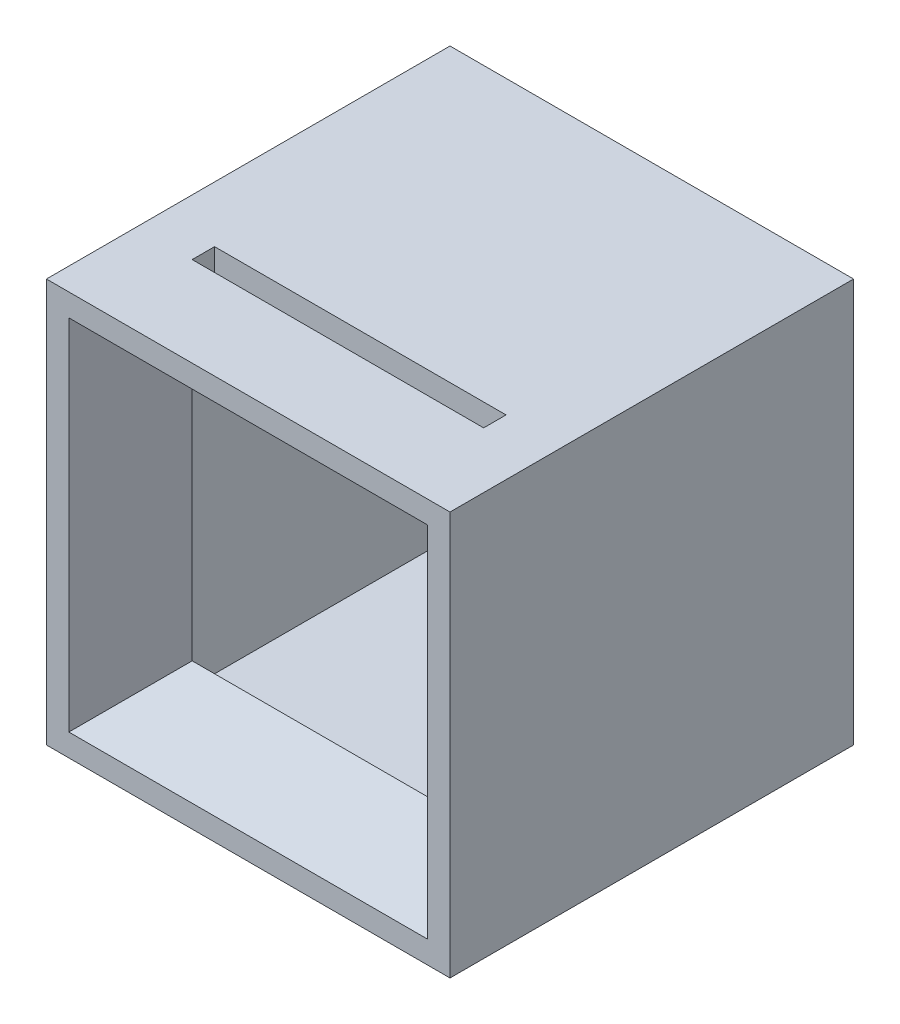
SolidWorks part; units mm, degrees
ref_plane "Front Plane" through (0, 0, 0) normal (0, 0, 1) x (1, 0, 0)
ref_plane "Top Plane" through (0, 0, 0) normal (0, 1, 0) x (1, 0, 0)
ref_plane "Right Plane" through (0, 0, 0) normal (1, 0, 0) x (0, 0, -1)
sketch "Sketch1" plane through (0, 0, 0) normal (0, 0, 1) x (1, 0, 0)
  line L1 (0, 0) -> (457.2, 0)
  line L2 (0, 0) -> (0, 457.2)
  line L3 (0, 457.2) -> (457.2, 457.2)
  line L4 (457.2, 0) -> (457.2, 457.2)
  dimension "D1" = 457.2
  dimension "D2" = 457.2
extrude "Boss-Extrude1" add sketch "Sketch1" along normal blind 457.2
sketch "Sketch2" plane through (0, 0, 457.2) normal (0, 0, 1) x (1, 0, 0)
  line L0 (457.2, 457.2) -> (0, 457.2) construction
  line L1 (25.4, 25.4) -> (431.8, 25.4)
  line L2 (25.4, 25.4) -> (25.4, 431.8)
  line L3 (25.4, 431.8) -> (431.8, 431.8)
  line L4 (431.8, 25.4) -> (431.8, 431.8)
  line L5 (457.2, 0) -> (457.2, 457.2) construction
  line L6 (0, 457.2) -> (0, 0) construction
  line L7 (0, 0) -> (457.2, 0) construction
  dimension "D1" = 25.4
  dimension "D2" = 25.4
  dimension "D3" = 25.4
  dimension "D4" = 25.4
ref_plane "Plane1" through (0, 0, 355.6) normal (0, 0, 1) x (1, 0, 0)
sketch "Sketch3" plane through (0, 0, 355.6) normal (0, 0, 1) x (1, 0, 0)
  line L0 (25.4, 431.8) -> (431.8, 431.8) construction
  line L1 (63.5, 63.5) -> (393.7, 63.5)
  line L2 (63.5, 63.5) -> (63.5, 393.7)
  line L3 (63.5, 393.7) -> (393.7, 393.7)
  line L4 (393.7, 63.5) -> (393.7, 393.7)
  line L5 (431.8, 25.4) -> (431.8, 431.8) construction
  dimension "D1" = 330.2
  dimension "D2" = 330.2
  dimension "D3" = 38.1
  dimension "D4" = 38.1
loft "Cut-Loft1" cut profiles "Sketch2", "Sketch3"
sketch "Sketch4" plane through (0, 0, 355.6) normal (0, 0, 1) x (1, 0, 0)
  line L0 (393.7, 63.5) -> (393.7, 393.7) construction
  line L1 (63.5, 63.5) -> (393.7, 63.5) construction
  line L2 (63.5, 393.7) -> (63.5, 63.5) construction
  line L3 (393.7, 393.7) -> (63.5, 393.7) construction
  line L4 (393.7, 63.5) -> (393.7, 393.7)
  line L5 (63.5, 63.5) -> (393.7, 63.5)
  line L6 (63.5, 393.7) -> (63.5, 63.5)
  line L7 (393.7, 393.7) -> (63.5, 393.7)
extrude "Cut-Extrude1" cut sketch "Sketch4" against normal blind 457.2
sketch "Sketch5" plane through (0, 63.5, 0) normal (0, 1, 0) x (1, 0, 0)
  line L4 (393.7, 0) -> (63.5, 0)
  line L5 (63.5, 0) -> (63.5, -355.6)
  line L6 (63.5, -355.6) -> (393.7, -355.6)
  line L7 (393.7, -355.6) -> (393.7, 0)
  line L8 (393.7, 0) -> (63.5, 0)
  line L9 (63.5, 0) -> (63.5, -355.6)
  line L10 (63.5, -355.6) -> (393.7, -355.6)
  line L11 (393.7, -355.6) -> (393.7, 0)
  dimension "D1" = 0
extrude "Cut-Extrude2" cut sketch "Sketch5" against normal blind 25.4
sketch "Sketch7" plane through (0, 457.2, 0) normal (0, 1, 0) x (1, 0, 0)
  line L0 (-251.46, -355.6) -> (251.46, -355.6) construction
  line L1 (63.5, -355.6) -> (393.7, -355.6)
  line L2 (63.5, -355.6) -> (63.5, -330.2)
  line L3 (63.5, -330.2) -> (393.7, -330.2)
  line L4 (393.7, -355.6) -> (393.7, -330.2)
  line L5 (457.2, -457.2) -> (457.2, 0) construction
  dimension "D1" = 330.2
  dimension "D2" = 63.5
  dimension "D3" = 25.4
extrude "Cut-Extrude3" cut sketch "Sketch7" against normal through all both and the other way through all
